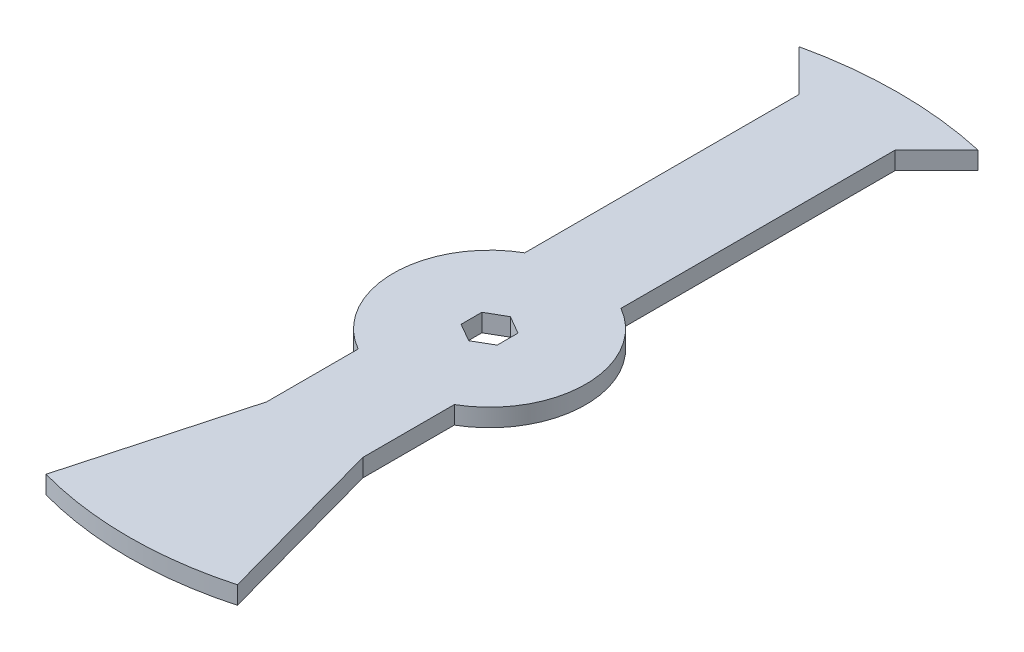
SolidWorks part; units mm, degrees
material "Plain Carbon Steel"
ref_plane "Front Plane" through (0, 0, 0) normal (0, 0, 1) x (1, 0, 0)
ref_plane "Top Plane" through (0, 0, 0) normal (0, 1, 0) x (1, 0, 0)
ref_plane "Right Plane" through (0, 0, 0) normal (1, 0, 0) x (0, 0, -1)
sketch "Sketch2" plane through (0, 0, 0) normal (0, 1, 0) x (1, 0, 0)
  line L0 (0, 0) -> (0, 107.95) construction
  line L1 (-12.7, 0) -> (12.7, 0)
  line L2 (12.7, 94.3995) -> (12.7, -94.3995)
  line L3 (-12.7, 94.3995) -> (-12.7, -94.3995)
  line L4 (0, 0) -> (25.2686, -91.8371) construction
  line L5 (0, 0) -> (0, -95.25) construction
  line L6 (-25.2686, -91.8371) -> (0, 0) construction
  line L7 (25.2686, -91.8371) -> (12.7, -46.1574)
  line L8 (-12.7, 94.3995) -> (-23.632, 105.3315)
  line L9 (-12.7, -46.1574) -> (-25.2686, -91.8371)
  line L11 (23.632, 105.3315) -> (12.7, 94.3995)
  circle A0 centre (0, 0) radius 107.95 construction
  circle A1 centre (0, 0) radius 95.25 construction
  circle A2 centre (0, 0) radius 25.4 construction
  arc A3 (-12.7, 21.997) -> (-12.7, -21.997) centre (0, 0) ccw
  arc A4 (12.7, 21.997) -> (12.7, -21.997) centre (0, 0) cw
  arc A5 (-23.632, 105.3315) -> (23.632, 105.3315) centre (0, 0) cw
  arc A6 (-25.2686, -91.8371) -> (25.2686, -91.8371) centre (0, 0) ccw
  point P8 (0, 0)
  dimension "D1" = 215.9
  dimension "D2" = 190.5
  dimension "D4" = 50.8
  dimension "D5" = 90
  dimension "D6" = 30.768
  dimension "D3" = 25.4
extrude "Boss-Extrude1" add sketch "Sketch2" along normal blind 4.699 contours L3 A6 L2 L1 | L9 A6 L3 | L2 A6 L7 | A4 L2 | L3 A3 | A5 L8 L3 L1 L2 L11
sketch "Sketch3" plane through (0, 4.699, 0) normal (0, 1, 0) x (1, 0, 0)
  line L1 (-4.7625, 2.7496) -> (-4.7625, -2.7496)
  line L2 (-4.7625, -2.7496) -> (0, -5.4993)
  line L3 (0, -5.4993) -> (4.7625, -2.7496)
  line L4 (4.7625, -2.7496) -> (4.7625, 2.7496)
  line L5 (4.7625, 2.7496) -> (0, 5.4993)
  line L6 (0, 5.4993) -> (-4.7625, 2.7496)
  circle A0 centre (0, 0) radius 4.7625 construction
  dimension "D1" = 9.525
extrude "Cut-Extrude1" cut sketch "Sketch3" against normal up to next
